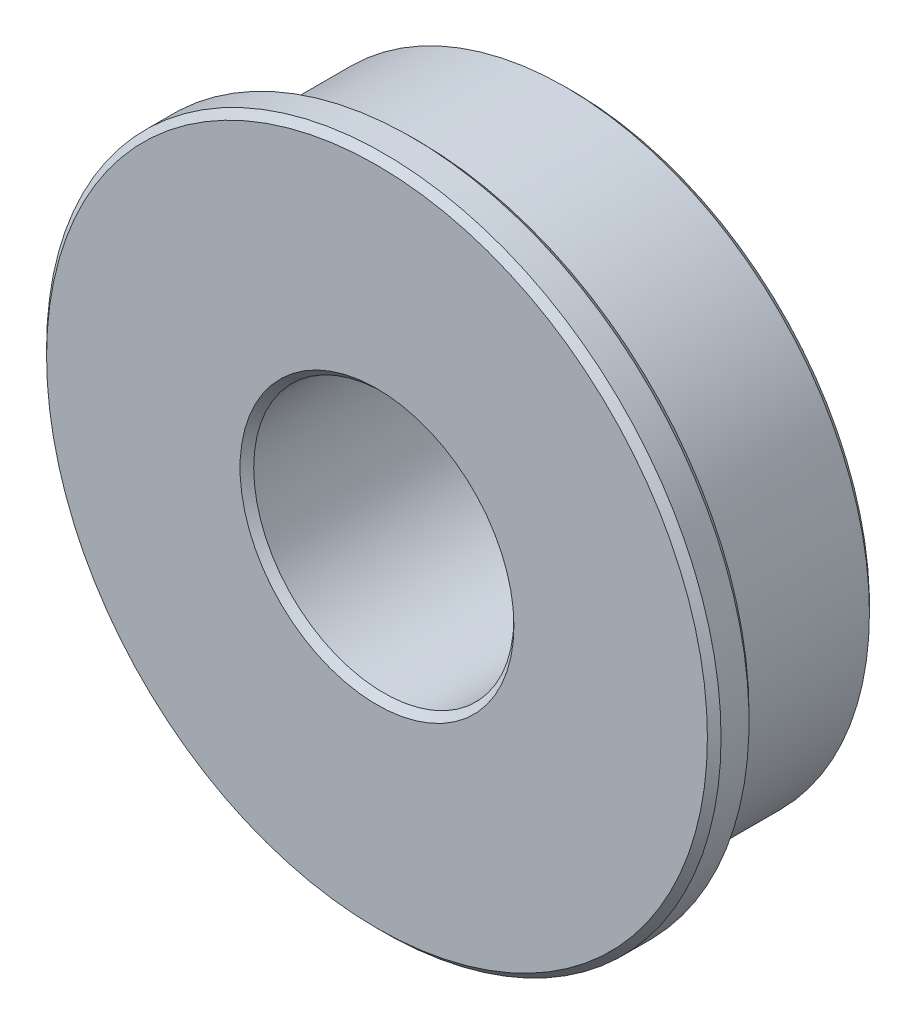
SolidWorks part; units mm, degrees
ref_plane "Front" through (0, 0, 0) normal (0, 0, 1) x (1, 0, 0)
ref_plane "Top" through (0, 0, 0) normal (0, 1, 0) x (1, 0, 0)
ref_plane "Right" through (0, 0, 0) normal (1, 0, 0) x (0, 0, -1)
sketch "Sketch2" plane through (0, 0, 0) normal (0, 1, 0) x (1, 0, 0)
  line L0 (0, 0) -> (0, -5.6388) construction
  line L23 (-4.7625, 0) -> (-11.1125, 0)
  line L25 (-4.7625, -7.1628) -> (-4.7625, 0)
  line L27 (-12.3444, -7.1628) -> (-4.7625, -7.1628)
  line L29 (-12.3444, -5.6388) -> (-12.3444, -7.1628)
  line L31 (-11.1125, -5.6388) -> (-12.3444, -5.6388)
  line L32 (-11.1125, 0) -> (-11.1125, -5.6388)
  dimension "D1" = 4.7625
  dimension "D2" = 6.35
  dimension "D3" = 7.1628
  dimension "D4" = 1.524
  dimension "D5" = 7.5819
  dimension "D6" = 5.6388
revolve "Revolve1" add sketch "Sketch2" angle 360 about L0
chamfer "Chamfer1" distance 0.25 angle 45 5 edges at (-4.7625, 0, 0) (-11.1125, 0, 0) (-4.7625, 0, 7.1628) (-12.3444, 0, 5.6388) (-12.3444, 0, 7.1628)
